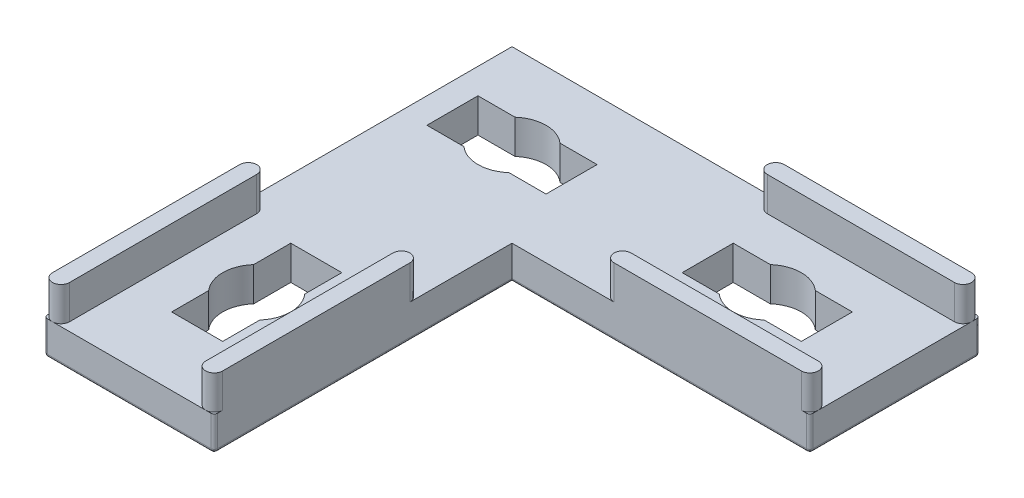
SolidWorks part; units mm, degrees
ref_plane "前视基准面" through (0, 0, 0) normal (0, 0, 1) x (1, 0, 0)
ref_plane "上视基准面" through (0, 0, 0) normal (0, 1, 0) x (1, 0, 0)
ref_plane "右视基准面" through (0, 0, 0) normal (1, 0, 0) x (0, 0, -1)
sketch "草图1" plane through (0, 0, 0) normal (0, 1, 0) x (1, 0, 0)
  line L0 (0, 0) -> (0, -27.5)
  line L1 (0, 0) -> (27.5, 0)
  line L2 (27.5, -10) -> (10, -10)
  line L3 (0, -27.5) -> (10, -27.5)
  line L4 (10, -10) -> (10, -27.5)
  line L6 (27.5, 0) -> (27.5, -10)
  dimension "D1" = 27.5
  dimension "D2" = 10
  dimension "D3" = 10
  dimension "D4" = 27.5
extrude "凸台-拉伸1" add sketch "草图1" along normal blind 2
sketch "草图2" plane through (0, 2, 0) normal (0, 1, 0) x (1, 0, 0)
  line L1 (27.5, -10) -> (27.5, 0) construction
  line L3 (27.5, -5) -> (22.2283, -5) construction
  line L6 (27, 0) -> (16, 0)
  line L7 (27, -1) -> (16, -1)
  line L8 (27, -9) -> (16, -9)
  line L9 (27, -10) -> (16, -10)
  line L11 (0, -27.5) -> (10, -27.5) construction
  line L13 (5, -27.5) -> (5, -24.5207) construction
  line L16 (1, -27) -> (1, -16)
  line L17 (0, -27) -> (0, -16)
  line L18 (9, -27) -> (9, -16)
  line L19 (10, -27) -> (10, -16)
  arc A0 (16, 0) -> (16, -1) centre (16, -0.5) ccw
  arc A1 (27, -1) -> (27, 0) centre (27, -0.5) ccw
  arc A2 (27, -9) -> (27, -10) centre (27, -9.5) cw
  arc A3 (16, -10) -> (16, -9) centre (16, -9.5) cw
  arc A4 (0, -16) -> (1, -16) centre (0.5, -16) cw
  arc A5 (0, -27) -> (1, -27) centre (0.5, -27) ccw
  arc A6 (10, -27) -> (9, -27) centre (9.5, -27) cw
  arc A7 (10, -16) -> (9, -16) centre (9.5, -16) ccw
extrude "凸台-拉伸2" add sketch "草图2" along normal blind 2
sketch "草图3" plane through (0, 2, 0) normal (0, 1, 0) x (1, 0, 0)
  line L0 (27.5, -5) -> (20, -5) construction
  line L1 (27.5, -9.5) -> (27.5, -0.5) construction
  line L2 (23.5, -3.5) -> (23.5, -6.5)
  line L3 (23.5, -3.5) -> (21.3229, -3.5)
  line L4 (23.5, -6.5) -> (21.3229, -6.5)
  line L5 (16.5, -3.5) -> (16.5, -6.5)
  line L6 (23.5, -3.5) -> (16.5, -6.5) construction
  line L7 (23.5, -6.5) -> (16.5, -3.5) construction
  line L8 (18.6771, -3.5) -> (16.5, -3.5)
  line L9 (18.6771, -6.5) -> (16.5, -6.5)
  arc A0 (18.6771, -6.5) -> (21.3229, -6.5) centre (20, -5) ccw
  arc A1 (21.3229, -3.5) -> (18.6771, -3.5) centre (20, -5) ccw
  dimension "D2" = 4
  dimension "D1" = 7.5
  dimension "D3" = 3
  dimension "D4" = 7
extrude "切除-拉伸1" cut sketch "草图3" against normal up to next
pattern_linear "阵列(线性)1" count 2 spacing 15 along (-1, 0, 0) of "切除-拉伸1"
sketch "草图4" plane through (0, 2, 0) normal (0, 1, 0) x (1, 0, 0)
  line L0 (5, -27.5) -> (5, -20) construction
  line L1 (0.5, -27.5) -> (9.5, -27.5) construction
  line L2 (6.5, -23.5) -> (3.5, -23.5)
  line L3 (6.5, -23.5) -> (6.5, -21.3229)
  line L4 (3.5, -23.5) -> (3.5, -21.3229)
  line L5 (6.5, -16.5) -> (3.5, -16.5)
  line L6 (6.5, -23.5) -> (3.5, -16.5) construction
  line L7 (3.5, -23.5) -> (6.5, -16.5) construction
  line L8 (6.5, -18.6771) -> (6.5, -16.5)
  line L9 (3.5, -18.6771) -> (3.5, -16.5)
  arc A0 (3.5, -18.6771) -> (3.5, -21.3229) centre (5, -20) ccw
  arc A1 (6.5, -21.3229) -> (6.5, -18.6771) centre (5, -20) ccw
  dimension "D4" = 4
  dimension "D1" = 7.5
  dimension "D2" = 3
  dimension "D3" = 7
extrude "切除-拉伸2" cut sketch "草图4" against normal up to next
fillet "圆角1" radius 0.2 10 edges at (27.5, 1, 0) (27.5, 1, 10) (0, 1, 27.5) (10, 1, 27.5) (5, 0, 27.5) (27.5, 0, 5) (10, 0, 18.75) (18.75, 0, 10) (0, 0, 13.75) (13.75, 0, 0)
